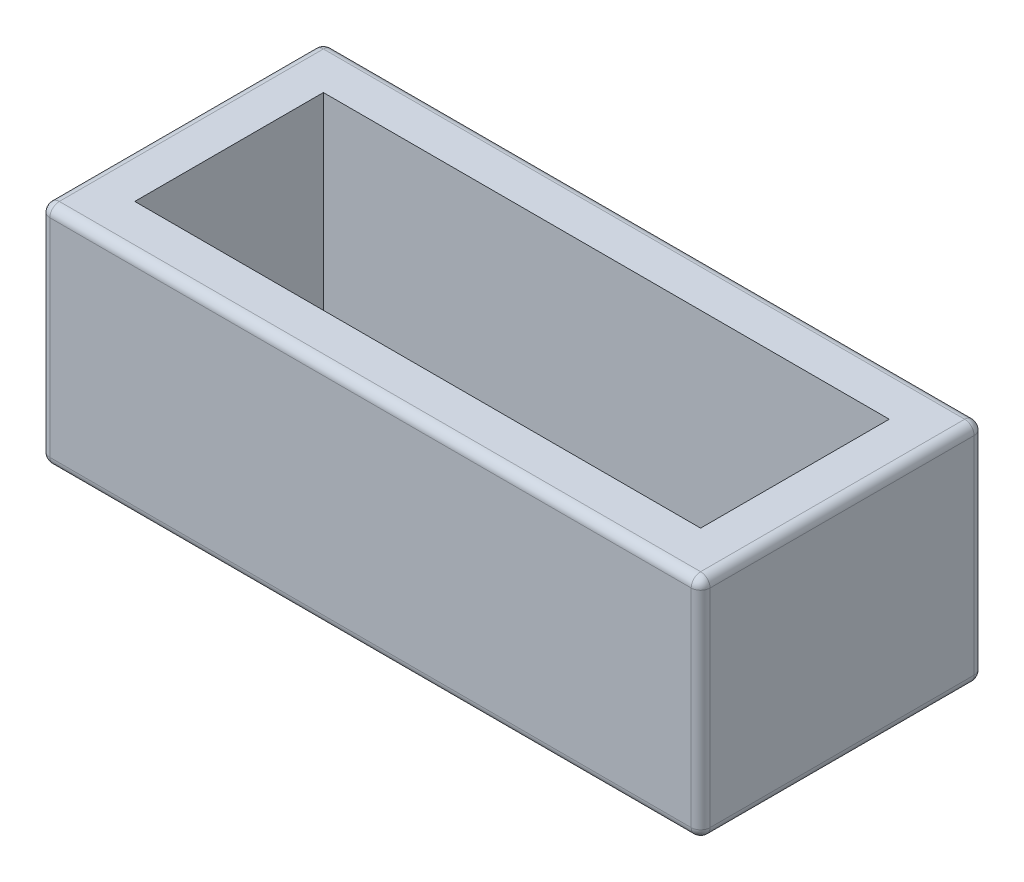
SolidWorks part; units mm, degrees
ref_plane "Front Plane" through (0, 0, 0) normal (0, 0, 1) x (1, 0, 0)
ref_plane "Top Plane" through (0, 0, 0) normal (0, 1, 0) x (1, 0, 0)
ref_plane "Right Plane" through (0, 0, 0) normal (1, 0, 0) x (0, 0, -1)
sketch "Sketch1" plane through (0, 0, 0) normal (0, 1, 0) x (1, 0, 0)
  line L1 (0, 0) -> (35, 0)
  line L2 (0, 0) -> (0, 15)
  line L3 (0, 15) -> (35, 15)
  line L4 (35, 0) -> (35, 15)
  dimension "D1" = 35
  dimension "D2" = 15
extrude "Boss-Extrude1" add sketch "Sketch1" along normal blind 12
shell "Shell1" thickness 2.5
sketch "Sketch2" plane through (0, 2.5, 0) normal (0, 1, 0) x (1, 0, 0)
  circle A0 centre (2.5, 12.5) radius 2
  circle A1 centre (32.5, 12.5) radius 1.9735
  circle A2 centre (32.5, 2.5) radius 1.9735
  circle A3 centre (2.5, 2.5) radius 1.9735
  dimension "D1" = 4
fillet "Fillet1" radius 0.5 12 edges at (17.5, 12, -15) (0, 6, -15) (0, 12, -7.5) (35, 12, -7.5) (35, 6, -15) (0, 6, 0) (17.5, 12, 0) (35, 6, 0) (17.5, 0, 0) (35, 0, -7.5) (17.5, 0, -15) (0, 0, -7.5)
sketch "Sketch3" plane through (0, 2.5, 0) normal (0, 1, 0) x (1, 0, 0)
  line L1 (2.5, 2.5) -> (32.5, 2.5)
  line L2 (2.5, 2.5) -> (2.5, 12.5)
  line L3 (2.5, 12.5) -> (32.5, 12.5)
  line L4 (32.5, 2.5) -> (32.5, 12.5)
extrude "Cut-Extrude1" cut sketch "Sketch3" against normal blind 0.5
